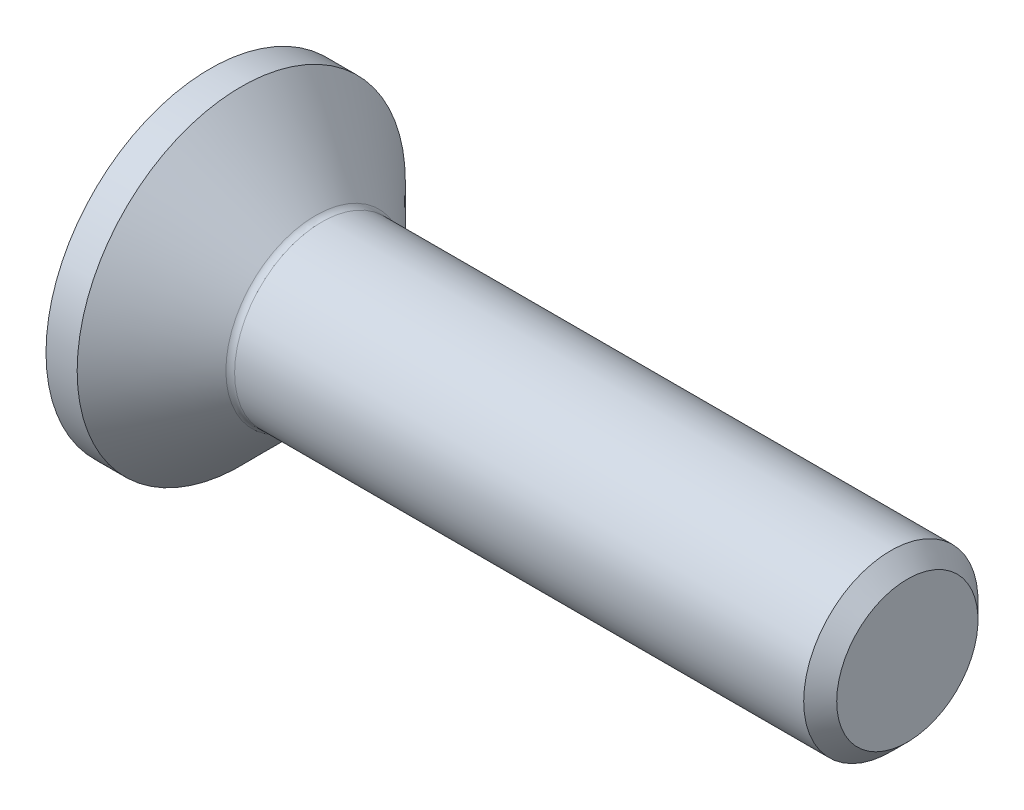
SolidWorks part; units mm, degrees
ref_plane "Front" through (0, 0, 0) normal (0, 0, 1) x (1, 0, 0)
ref_plane "Top" through (0, 0, 0) normal (0, 1, 0) x (1, 0, 0)
ref_plane "Right" through (0, 0, 0) normal (1, 0, 0) x (0, 0, -1)
sketch "Sketch1" plane through (0, 0, 0) normal (0, 0, 1) x (1, 0, 0)
  line L0 (0, 0) -> (0, 4.48)
  line L1 (0, 4.48) -> (2.48, 2)
  line L2 (2.48, 2) -> (16, 2)
  line L3 (16, 2) -> (16, 0)
  line L4 (16, 0) -> (0, 0)
  line L5 (-0.5871, 0) -> (5.4927, 0) construction
  dimension "l" = 16
  dimension "k" = 2.48
  dimension "d" = 4
  dimension "D1" = 45
revolve "Base" add sketch "Sketch1" angle 360 about L5
cosmetic thread "ThreadCosmetic1" parameters "b"=13.5, "D2"=3.242
sketch "Sketch2" plane through (0, 0, 0) normal (1, 0, 0) x (0, 0, -1)
  line L1 (1.4434, 0) -> (0.7217, 1.25)
  line L2 (0.7217, 1.25) -> (-0.7217, 1.25)
  line L3 (-0.7217, 1.25) -> (-1.4434, 0)
  line L4 (-1.4434, 0) -> (-0.7217, -1.25)
  line L5 (-0.7217, -1.25) -> (0.7217, -1.25)
  line L6 (0.7217, -1.25) -> (1.4434, 0)
  circle A0 centre (0, 0) radius 1.25 construction
  dimension "s" = 2.5
extrude "HexagonSocket" cut sketch "Sketch2" along normal blind 1.5
sketch "Sketch3" plane through (0, 0, 0) normal (0, 0, 1) x (1, 0, 0)
  line L0 (-0.4391, 0) -> (4.425, 0) construction
  line L1 (1.5, 0) -> (1.5, -1.25) construction
  line L2 (1.5, 1.25) -> (2.2217, 0)
  line L3 (2.2217, 0) -> (1.5, -1.25) construction
  line L4 (1.5, 1.25) -> (1.5, 0)
  line L5 (1.5, 0) -> (2.2217, 0)
  line L7 (1.5, 1.25) -> (1.5, 0) construction
  dimension "D1" = 120
revolve "Cut-Revolve1" cut sketch "Sketch3" angle 360 about L0
fillet "HeadFillet" radius 0.2 1 edges at (2.48, 0, 2)
chamfer "Chamfer" distance 0.379 angle 45 1 edges at (16, 0, 2)
sketch "Sketch4" plane through (0, 0, 0) normal (0, 1, 0) x (1, 0, 0)
  line L0 (11.8531, 0) -> (-2.694, 0) construction
  line L1 (-2, 8.765) -> (3, 8.765)
  line L2 (-2, 8.765) -> (-2, 3.765)
  line L3 (-2, 3.765) -> (3, 3.765)
  line L4 (3, 8.765) -> (3, 3.765)
  line L5 (0, 4.48) -> (0, -4.48) construction
  dimension "dk" = 7.53
  dimension "D2" = 2
  dimension "D3" = 5
  dimension "D4" = 5
revolve "Cut-Revolve2" cut sketch "Sketch4" angle 360 about L0
sketch "Sketch5" plane through (0, 0, 0) normal (0, 0, 1) x (1, 0, 0)
  line L0 (15.621, 1.6718) -> (15.8105, 2)
  line L1 (15.8105, 2) -> (15.8105, 2.379)
  line L2 (15.8105, 2.379) -> (15.4315, 2.379)
  line L3 (15.4315, 2.379) -> (15.4315, 2)
  line L4 (15.4315, 2) -> (15.621, 1.6718)
  line L5 (0, 0) -> (10.6885, 0) construction
  line L6 (15.621, 2) -> (15.621, -2) construction
  dimension "D1" = 4
  dimension "D2" = 0.379
revolve "Cut-Revolve10" [suppressed] cut sketch "Sketch5" angle 360 about L5
pattern_linear "LPattern10" [suppressed] count 30 spacing 0.4548 along (1, 0, 0)
equation "\"D1@Chamfer\" = (  \"d@Sketch1\" - \"D2@ThreadCosmetic1\" )  / 2"
equation "\"D1@Sketch5\" = \"d@Sketch1\""
equation "\"D2@Sketch5\" =  ( \"d@Sketch1\" - \"D2@ThreadCosmetic1\" )  / 2"
equation "\"D3@LPattern10\" = \"D2@Sketch5\" * 1.2"
equation "\"D1@LPattern10\" = \"b@ThreadCosmetic1\" / \"D3@LPattern10\""
